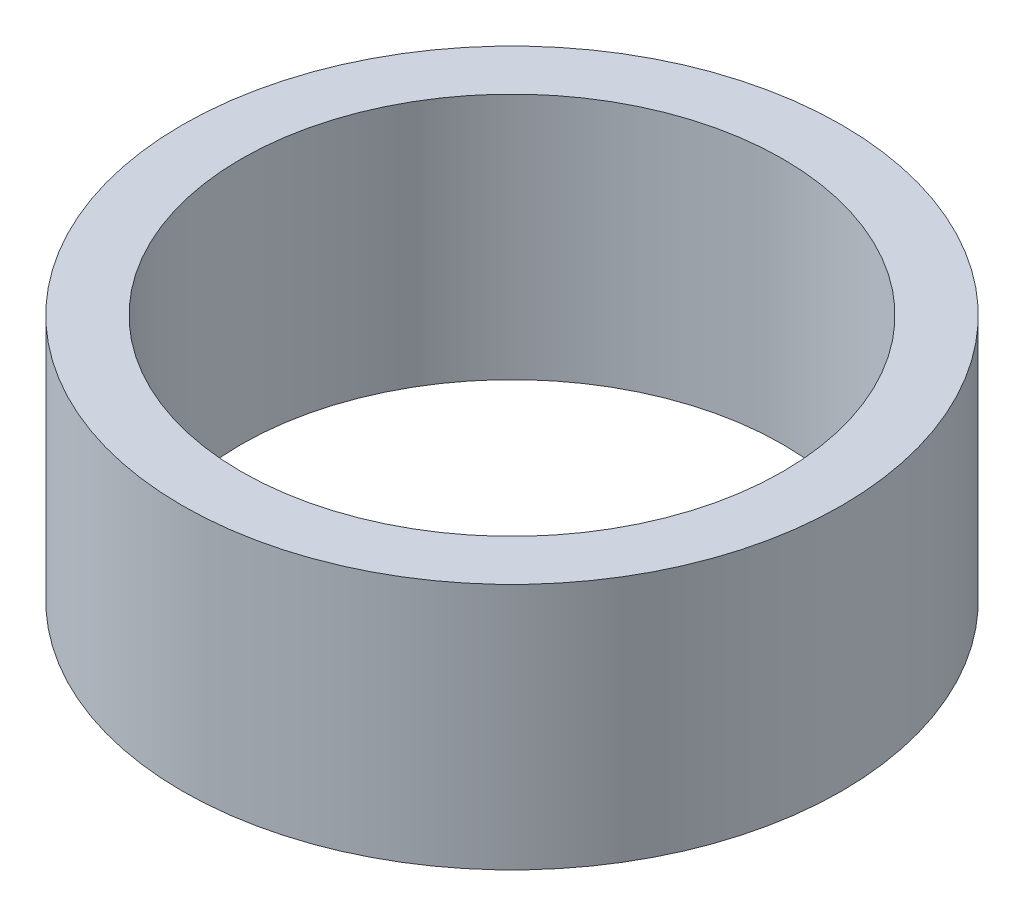
SolidWorks part; units mm, degrees
ref_plane "Front Plane" through (0, 0, 0) normal (0, 0, 1) x (1, 0, 0)
ref_plane "Top Plane" through (0, 0, 0) normal (0, 1, 0) x (1, 0, 0)
ref_plane "Right Plane" through (0, 0, 0) normal (1, 0, 0) x (0, 0, -1)
sketch "Sketch1" plane through (0, 0, 0) normal (0, 1, 0) x (1, 0, 0)
  circle A0 centre (0, 0) radius 11.5
  circle A1 centre (0, 0) radius 14
  dimension "D1" = 23
  dimension "D2" = 28
extrude "Boss-Extrude1" add sketch "Sketch1" along normal blind 10.5
